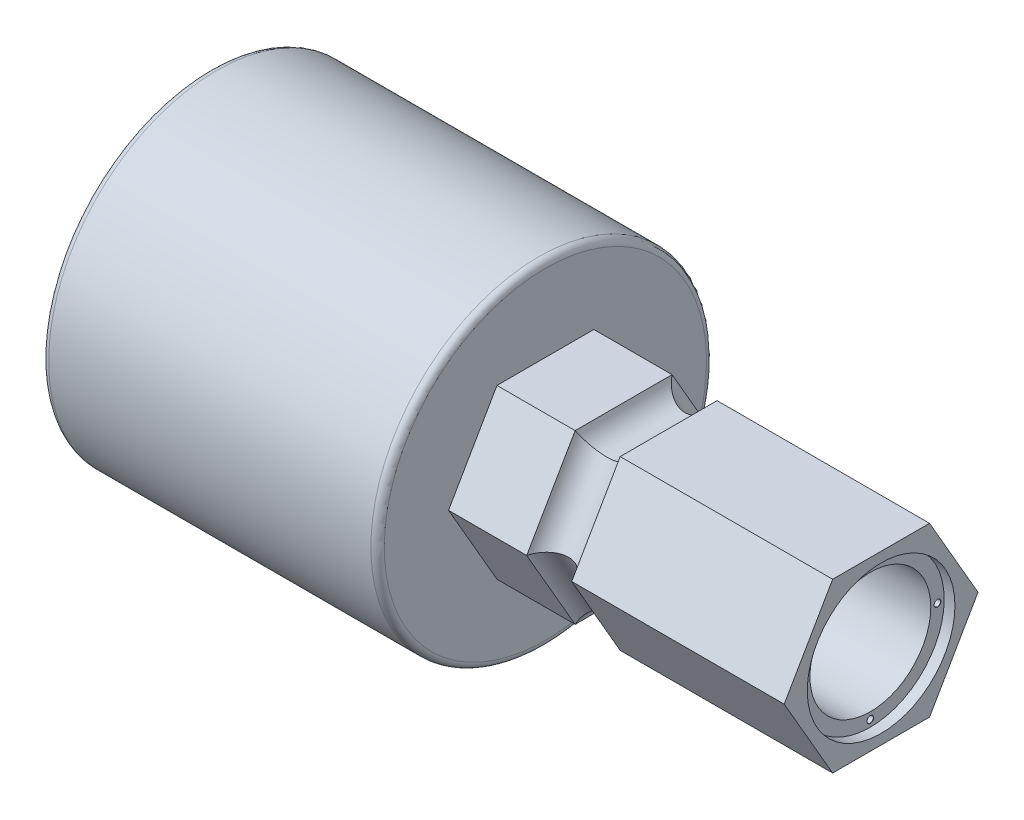
SolidWorks part; units mm, degrees
ref_plane "Front Plane" through (0, 0, 0) normal (0, 0, 1) x (1, 0, 0)
ref_plane "Top Plane" through (0, 0, 0) normal (0, 1, 0) x (1, 0, 0)
ref_plane "Right Plane" through (0, 0, 0) normal (1, 0, 0) x (0, 0, -1)
sketch "Sketch1" plane through (0, 0, 0) normal (0, 0, 1) x (1, 0, 0)
  line L0 (0, 0) -> (0, 2)
  line L1 (1, 3) -> (49, 3)
  line L2 (50, 2) -> (50, -12)
  line L3 (50, -12) -> (48, -12)
  line L4 (47, -11) -> (47, -1)
  line L5 (46, 0) -> (0, 0)
  line L6 (50, -12) -> (50, -22)
  line L7 (50, -22) -> (-16.531, -22) construction
  arc A0 (48, -12) -> (47, -11) centre (48, -11) cw
  arc A1 (47, -1) -> (46, 0) centre (46, -1) ccw
  arc A2 (50, 2) -> (49, 3) centre (49, 2) ccw
  arc A3 (0, 2) -> (1, 3) centre (1, 2) cw
  point P12 (47, -12)
  point P17 (50, 3)
  point P20 (0, 3)
  dimension "D6" = 1
  dimension "D1" = 3
  dimension "D2" = 3
  dimension "D3" = 50
  dimension "D4" = 15
  dimension "D5" = 10
revolve "Revolve1" add sketch "Sketch1" angle 360 about L7
sketch "Sketch2" plane through (50, 0, 0) normal (1, 0, 0) x (0, 0, -1)
  line L1 (14.4338, -22) -> (7.2169, -9.5)
  line L2 (7.2169, -9.5) -> (-7.2169, -9.5)
  line L3 (-7.2169, -9.5) -> (-14.4338, -22)
  line L4 (-14.4338, -22) -> (-7.2169, -34.5)
  line L5 (-7.2169, -34.5) -> (7.2169, -34.5)
  line L6 (7.2169, -34.5) -> (14.4338, -22)
  line L7 (11.547, -22) -> (5.7735, -12)
  line L8 (5.7735, -12) -> (-5.7735, -12)
  line L9 (-5.7735, -12) -> (-11.547, -22)
  line L10 (-11.547, -22) -> (-5.7735, -32)
  line L11 (-5.7735, -32) -> (5.7735, -32)
  line L12 (5.7735, -32) -> (11.547, -22)
  circle A0 centre (0, -22) radius 12.5 construction
  circle A1 centre (0, -22) radius 10 construction
  dimension "D1" = 25
  dimension "D3" = 20
  dimension "D2" = 12.5
  dimension "D4" = 10
extrude "Boss-Extrude3" add sketch "Sketch2" along normal blind 50
ref_plane "Plane1" through (0, -8.5, 0) normal (0, 1, 0) x (1, 0, 0)
sketch "Sketch3" plane through (0, -8.5, 0) normal (0, 1, 0) x (1, 0, 0)
  line L0 (65, 7.2169) -> (65, -7.2169)
  line L1 (100, 7.2169) -> (50, 7.2169) construction
  line L2 (100, -7.2169) -> (50, -7.2169) construction
  line L3 (65, -7.2169) -> (68.5, -7.2169)
  line L4 (68.5, -7.2169) -> (68.5, 7.2169)
  line L5 (68.5, 7.2169) -> (65, 7.2169)
  line L6 (50, 7.2169) -> (50, -7.2169) construction
  dimension "D1" = 3.5
  dimension "D2" = 15
ref_plane "Plane3" through (47, 0, 0) normal (-1, 0, 0) x (0, 0, 1)
sketch "Sketch6" plane through (47, 0, 0) normal (-1, 0, 0) x (0, 0, 1)
  circle A0 centre (0, -22) radius 9
  circle A1 centre (0, -22) radius 12.5
  dimension "D1" = 18
  dimension "D2" = 25
extrude "Boss-Extrude4" add sketch "Sketch6" along normal up to surface (53 mm away)
revolve "Cut-Revolve3" cut sketch "Sketch3" angle 360 about L0
pattern_circular "CirPattern4" count 6 over 360 of "Cut-Revolve3"
fillet "Fillet1" radius 1 1 edges at (47, -31, 0)
sketch "Sketch8" plane through (100, 0, 0) normal (1, 0, 0) x (0, 0, -1)
  circle A0 centre (0, -22) radius 11
  dimension "D1" = 22
extrude "Cut-Extrude1" cut sketch "Sketch8" against normal blind 1.6
sketch "Sketch12" plane through (98.4, 0, 0) normal (1, 0, 0) x (0, 0, -1)
  circle A0 centre (0, -22) radius 9 construction
  circle A3 centre (0, -22) radius 11 construction
  point P0 (0, -12)
  point P3 (0, 0)
  dimension "D2" = 10
  dimension "D1" = 10
hole_wizard "Tap Drill for M1.2x0.25 Tap1" positions "Sketch12" profile "Sketch10" hole size "M1.2x0.25" standard "ANSI Metric"
sketch "Sketch10" plane through (98.4, -12, 0) normal (0, 1, 0) x (0, 0, -1)
  line L0 (0, 0) -> (0, 2.2854)
  line L1 (0, 2.2854) -> (0.475, 2)
  line L2 (0.475, 2) -> (0.475, 0.025)
  line L3 (0.475, 0.025) -> (0.5, 0)
  line L5 (0.5, 0) -> (0, 0)
  line L6 (-0.475, 0.025) -> (-0.5, 0) construction
  line L10 (0, 2.2854) -> (-0.475, 2) construction
  line L11 (0, -6.35) -> (0, 107.95) construction
  dimension "Hole Dia." = 0.95
  dimension "Hole Depth" = 2
  dimension "Near C'Sink Dia." = 1
  dimension "Near C'Sink Angle" = 90
  dimension "Drill Angle" = 118
pattern_circular "CirPattern5" count 4 over 360 about axis through (0, -22, 0) along (1, 0, 0) of "Tap Drill for M1.2x0.25 Tap1"
